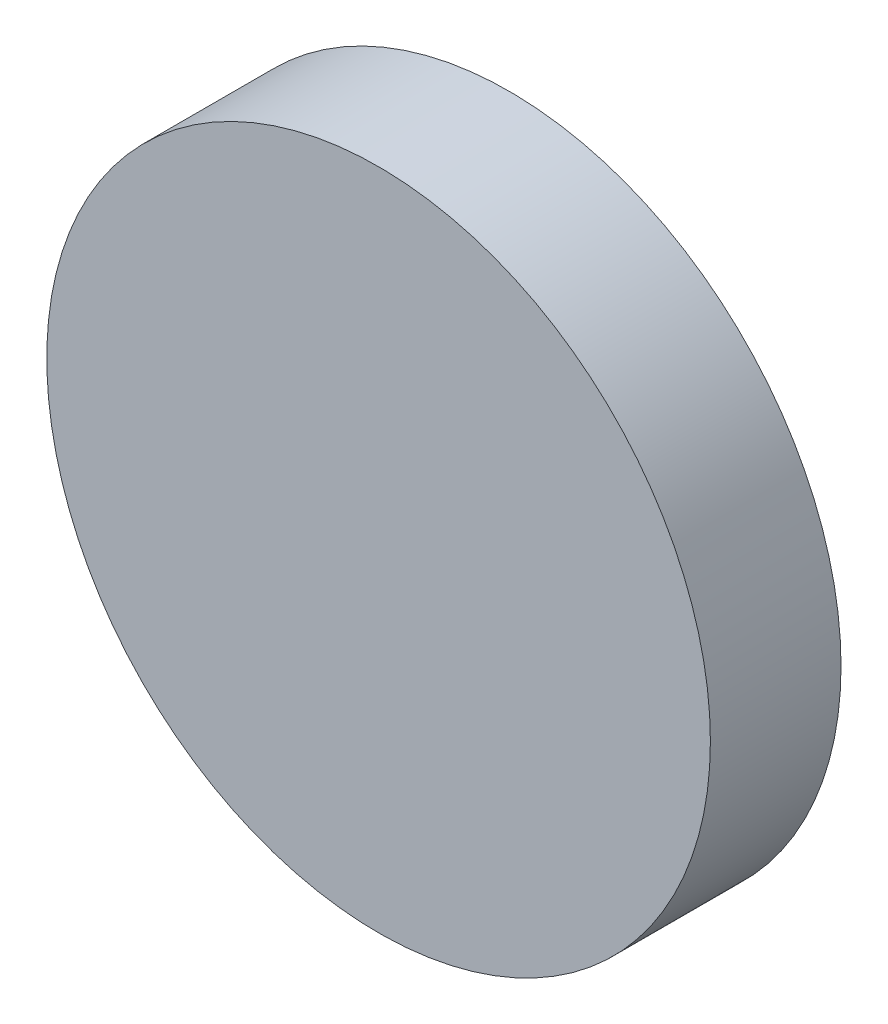
SolidWorks part; units mm, degrees
ref_plane "Front Plane" through (0, 0, 0) normal (0, 0, 1) x (1, 0, 0)
ref_plane "Top Plane" through (0, 0, 0) normal (0, 1, 0) x (1, 0, 0)
ref_plane "Right Plane" through (0, 0, 0) normal (1, 0, 0) x (0, 0, -1)
sketch "Sketch1" plane through (0, 0, 0) normal (0, 0, 1) x (1, 0, 0)
  circle A0 centre (0, 0) radius 25.4
extrude "Boss-Extrude1" add sketch "Sketch1" along normal blind 10
